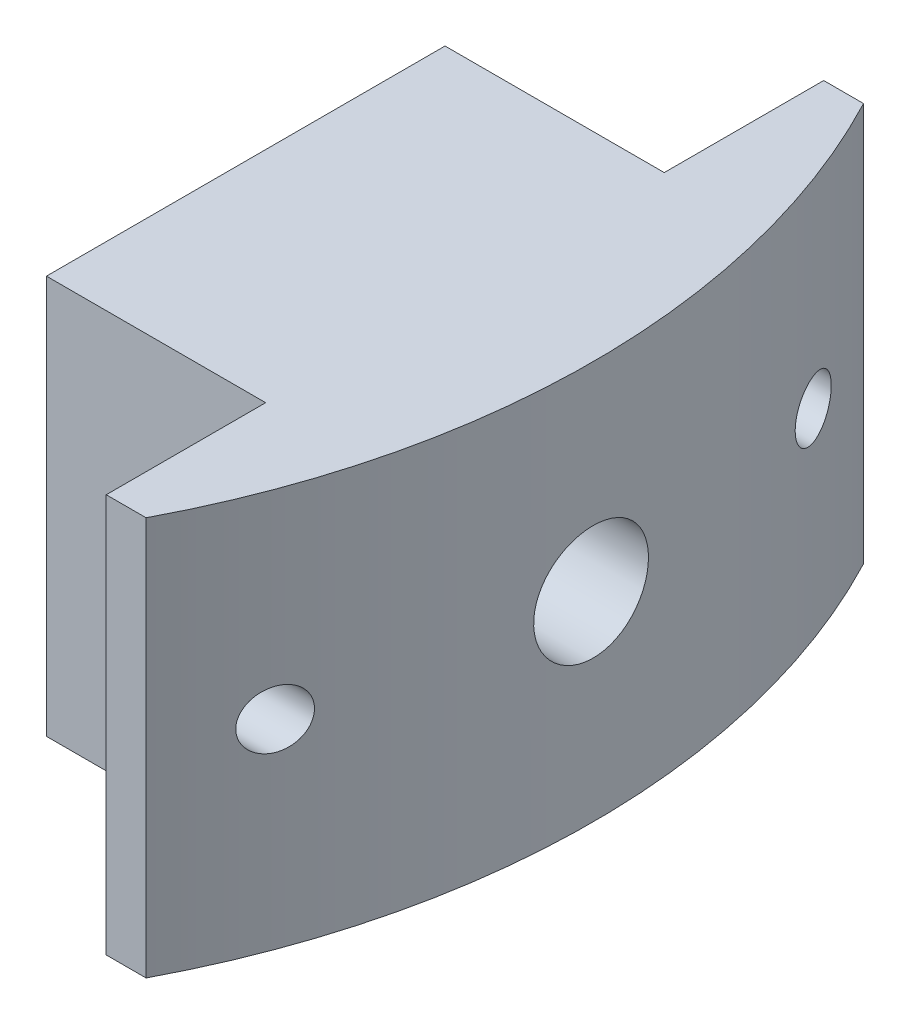
SolidWorks part; units mm, degrees
material "Plain Carbon Steel"
ref_plane "Front Plane" through (0, 0, 0) normal (0, 0, 1) x (1, 0, 0)
ref_plane "Top Plane" through (0, 0, 0) normal (0, 1, 0) x (1, 0, 0)
ref_plane "Right Plane" through (0, 0, 0) normal (1, 0, 0) x (0, 0, -1)
sketch "Sketch2" plane through (0, 0, 0) normal (0, 1, 0) x (1, 0, 0)
  line L0 (43.5809, 22.86) -> (43.5809, -22.86)
  line L1 (41.0409, 12.7) -> (41.0409, -12.7)
  line L2 (43.5809, 22.86) -> (41.0409, 22.86)
  line L3 (43.5809, 22.86) -> (43.5809, -22.86)
  line L4 (43.5809, -22.86) -> (41.0409, -22.86)
  line L5 (41.0409, 22.86) -> (41.0409, -22.86)
  line L6 (41.0409, 12.7) -> (27.0709, 12.7)
  line L11 (27.0709, 12.7) -> (27.0709, -12.7)
  line L12 (27.0709, -12.7) -> (41.0409, -12.7)
  line L13 (0, 0) -> (29.3279, 0) construction
  line L14 (0, 0) -> (47.5356, -12.7371) construction
  arc A0 (43.5809, -22.86) -> (43.5809, 22.86) centre (0, 0) ccw
  point P9 (41.0409, 0)
  dimension "D1" = 49.2125
  dimension "D2" = 45.72
  dimension "D3" = 2.54
  dimension "D4" = 25.4
  dimension "D5" = 13.97
  dimension "D6" = 15
extrude "Boss-Extrude1" add sketch "Sketch2" along normal blind 25.4 contours L11 L12 L1 L6 | L2 L5 L1 L4 L0 | L0 A0
ref_plane "Plane1" through (49.2125, 0, 0) normal (1, 0, 0) x (0, 0, -1)
sketch "Sketch4" plane through (27.0709, 0, 0) normal (-1, 0, 0) x (0, 0, 1)
  line L4 (-12.7, 0) -> (12.7, 25.4) construction
  line L5 (-12.7, 0) -> (12.7, 0) construction
  line L6 (-12.7, 25.4) -> (-12.7, 0) construction
  line L7 (-12.7, 25.4) -> (12.7, 0) construction
  line L8 (12.7, 25.4) -> (12.7, 0) construction
  line L9 (12.7, 25.4) -> (12.7, 0) construction
  circle A0 centre (0, 12.7) radius 3.81
  circle A1 centre (0, 12.7) radius 1.27
  point P15 (0, 12.7)
  dimension "D1" = 7.62
  dimension "D2" = 2.54
extrude "Cut-Extrude2" cut sketch "Sketch4" against normal up to next contours A1
sketch "Sketch11" plane through (41.0409, 0, 0) normal (-1, 0, 0) x (0, 0, 1)
  circle A2 centre (0, 12.7) radius 3.6576
  dimension "D3" = 7.3152
extrude "Cut-Extrude4" cut sketch "Sketch11" along normal blind 12.7 from surface at -8.1716 contours A2 starting at plane "Plane1"
sketch "Sketch13" plane through (49.2125, 0, 0) normal (1, 0, 0) x (0, 0, -1)
  line L1 (-6.2992, 12.7) -> (-7.6327, 12.7) construction
  line L2 (-6.2992, 12.7) -> (-4.9657, 12.7) construction
  line L4 (0, 12.7) -> (-22.86, 12.7) construction
  line L5 (-22.86, 25.4) -> (-22.86, 0) construction
  circle A0 centre (0, 12.7) radius 4.9657
  circle A1 centre (0, 12.7) radius 7.6327
  circle A2 centre (0, 12.7) radius 6.2992 construction
  dimension "D1" = 12.5984
  dimension "D2" = 2.667
wrap "Wrap3" [suppressed] sketch "Sketch13" source sketch "Sketch13" thickness 1.3208 parameters "D1"=1.3208
sketch "Sketch15" plane through (0, 0, 0) normal (1, 0, 0) x (0, 0, -1)
  line L0 (-22.86, 12.7) -> (22.86, 12.7) construction
  line L1 (0, 0) -> (0, 25.4) construction
  line L4 (-22.86, 0) -> (22.86, 0)
  line L5 (22.86, 0) -> (22.86, 25.4)
  line L6 (22.86, 25.4) -> (-22.86, 25.4)
  line L7 (-22.86, 25.4) -> (-22.86, 0)
  line L8 (-22.86, 0) -> (22.86, 0)
  line L9 (22.86, 0) -> (22.86, 25.4)
  line L10 (22.86, 25.4) -> (-22.86, 25.4)
  line L11 (-22.86, 25.4) -> (-22.86, 0)
  circle A0 centre (-17.145, 12.7) radius 1.8288
  circle A1 centre (17.145, 12.7) radius 1.8288
  dimension "D2" = 3.6576
  dimension "D3" = 5.715
  dimension "D1" = 0
extrude "Cut-Extrude5" cut sketch "Sketch15" along normal up to surface (46.7684 mm away) contours L0 A0 | A1
equation "\"Middle Coupler Inner Daimeter\"= 3.875in"
equation "\"Middle Coupler  Wall Thickness\" = 0.25in"
equation "\"Middle Coupler Bottom Thickness\"= 0.2in"
equation "\"Bearing Rail Offset\"= 0.45in"
equation "\"3-56 UNF Tap\"= 0.089in"
equation "\"3-48 Tap\"= 0.079in"
equation "\"3-56 UNF Clearance\"= 0.104in"
equation "\"3-48 Clearance\" = 0.104in"
equation "\"Ball Bearing Distance\"= 0.03in"
equation "\"TCA Outer Diameter\" = 6in"
equation "\"Interstage Aeroframe Wall Thickness\" = 0.072in"
equation "\"Compression Spring OD\"= 0.42in"
equation "\"10-24 Tap\"= 0.157in"
equation "\"10-24 Clearance\"= 0.196in"
equation "\"Lower Stage Fuselage Wall Thickness\" = 0.25in"
equation "\"6-32 Tap\" = 0.107in"
equation "\"6-32 Clearance\" = 0.144"
equation "\"1/4-20 Tap\" = 0.201in"
equation "\"12-24 Tap\" = 0.177in"
equation "\"D1@Sketch2\"=\"Middle Coupler Inner Daimeter\"/2"
equation "\"D2@Sketch15\"=\"6-32 Clearance\""
